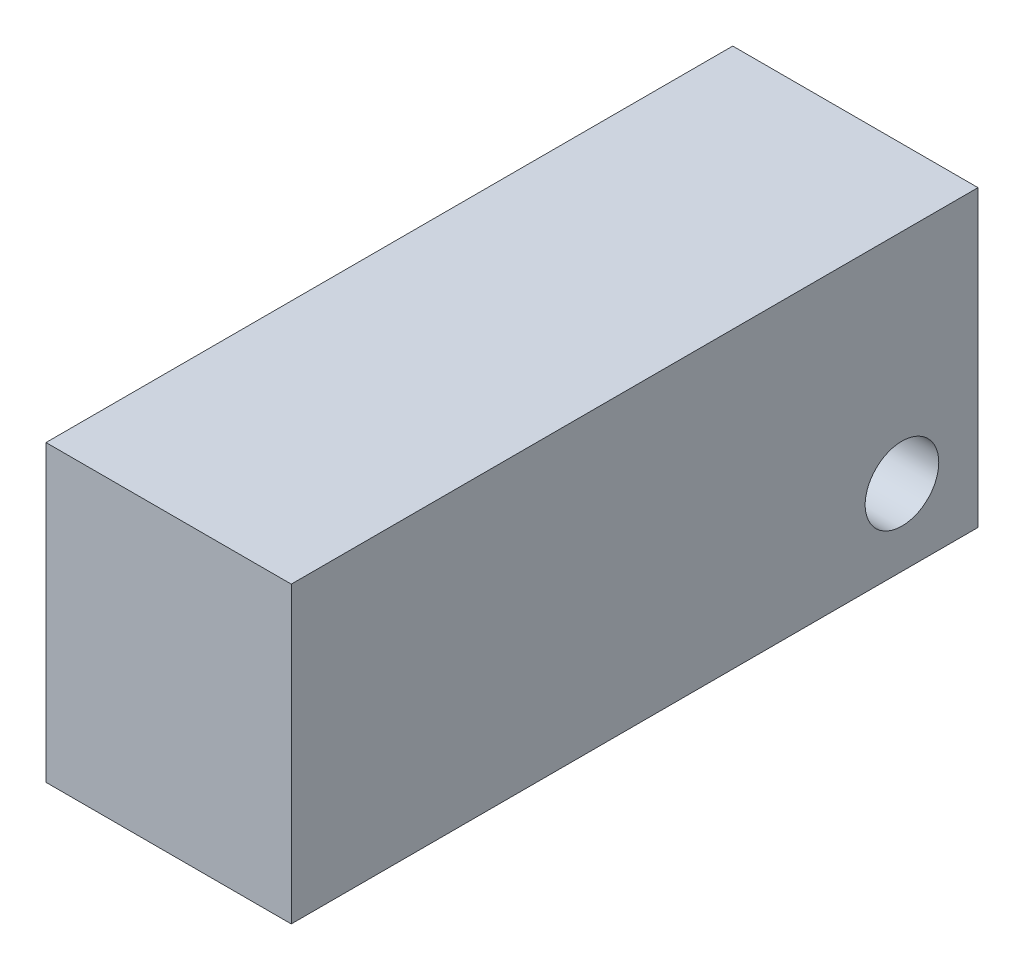
SolidWorks part; units mm, degrees
ref_plane "前视基准面" through (0, 0, 0) normal (0, 0, 1) x (1, 0, 0)
ref_plane "上视基准面" through (0, 0, 0) normal (0, 1, 0) x (1, 0, 0)
ref_plane "右视基准面" through (0, 0, 0) normal (1, 0, 0) x (0, 0, -1)
other "Configuration Table"
sketch "草图1" plane through (0, 0, 0) normal (1, 0, 0) x (0, 0, -1)
  line L1 (0, 0) -> (-28, 0)
  line L2 (0, 0) -> (0, 12)
  line L3 (0, 12) -> (-28, 12)
  line L4 (-28, 0) -> (-28, 12)
  circle A0 centre (-3.1, 3.1) radius 1.5
  dimension "D3" = 3
  dimension "D5" = 3.1
  dimension "D1" = 28
  dimension "D2" = 12
  dimension "D4" = 3.1
extrude "凸台-拉伸1" add sketch "草图1" along normal blind 10
